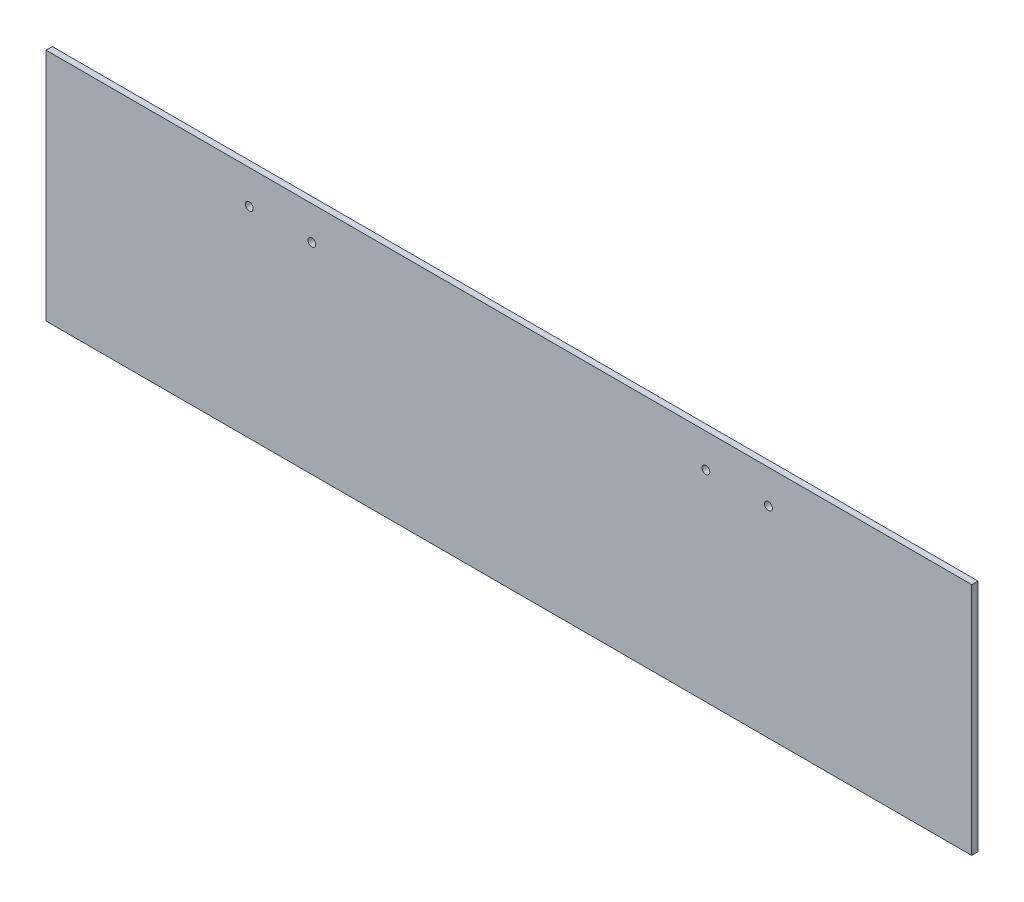
SolidWorks part; units mm, degrees
ref_plane "Front Plane" through (0, 0, 0) normal (0, 0, 1) x (1, 0, 0)
ref_plane "Top Plane" through (0, 0, 0) normal (0, 1, 0) x (1, 0, 0)
ref_plane "Right Plane" through (0, 0, 0) normal (1, 0, 0) x (0, 0, -1)
sketch "Sketch1" plane through (0, 0, 0) normal (0, 0, 1) x (1, 0, 0)
  line L1 (296, 150) -> (-296, 150)
  line L2 (296, 150) -> (296, 0)
  line L3 (296, 0) -> (-296, 0)
  line L4 (-296, 150) -> (-296, 0)
  line L5 (296, 150) -> (-296, 0) construction
  line L6 (296, 0) -> (-296, 150) construction
  point P0 (0, 75)
  point P95 (0, 0)
  dimension "D1" = 592
  dimension "D2" = 150
extrude "Boss-Extrude1" add sketch "Sketch1" along normal mid plane 4
sketch "Sketch2" plane through (0, 0, 2) normal (0, 0, 1) x (1, 0, 0)
  line L0 (-273.6263, 128.5) -> (255.9857, 128.5) construction
  line L1 (296, 150) -> (-296, 150) construction
  line L2 (0, 201.8168) -> (0, -51.0328) construction
  line L3 (-296, 150) -> (-296, 0) construction
  point P7 (-166, 128.5)
  point P8 (-126, 128.5)
  point P11 (126, 128.5)
  point P12 (166, 128.5)
  dimension "D1" = 21.5
  dimension "D2" = 40
  dimension "D3" = 130
hole_wizard "Tap Drill for M6 Tap1" positions "Sketch3" profile "Sketch4" hole size "M6" standard "ISO" end condition through all
sketch "Sketch3" plane through (0, 0, 2) normal (0, 0, 1) x (1, 0, 0)
  point P0 (-166, 128.5)
  point P3 (-126, 128.5)
  point P6 (126, 128.5)
  point P9 (166, 128.5)
sketch "Sketch4" plane through (-166, 128.5, 2) normal (1, 0, 0) x (0, -1, 0)
  line L0 (0, 0) -> (0, 4)
  line L1 (0, 4) -> (2.5, 4)
  line L2 (2.5, 4) -> (2.5, 0)
  line L5 (2.5, 0) -> (0, 0)
  line L11 (0, -6.35) -> (0, 107.95) construction
  dimension "Thru Hole Dia." = 5
  dimension "Thru Hole Depth" = 4
